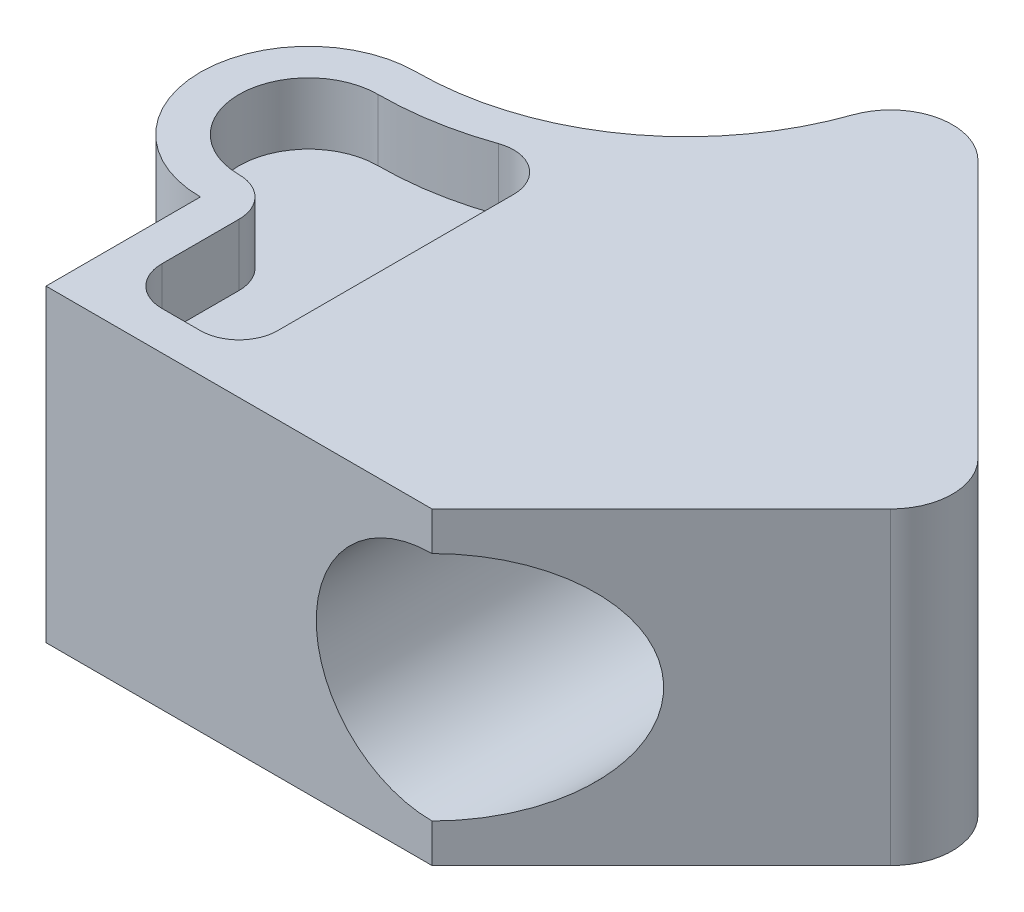
SolidWorks part; units mm, degrees
material "Alliage 1060"
ref_plane "Plan de face" through (0, 0, 0) normal (0, 0, 1) x (1, 0, 0)
ref_plane "Plan de dessus" through (0, 0, 0) normal (0, 1, 0) x (1, 0, 0)
ref_plane "Plan de droite" through (0, 0, 0) normal (1, 0, 0) x (0, 0, -1)
sketch "Esquisse1" plane through (0, 0, 0) normal (0, 1, 0) x (1, 0, 0)
  line L0 (0, 0) -> (50, 0)
  line L1 (50, 0) -> (79.6985, 29.6985)
  line L2 (0, 0) -> (0, 20)
  line L3 (79.6985, 41.0122) -> (46.2469, 74.4637)
  arc A0 (0, 20) -> (0, 48) centre (0, 34) cw
  arc A1 (0, 48) -> (33.0384, 71.4475) centre (0, 83) ccw
  arc A2 (79.6985, 29.6985) -> (79.6985, 41.0122) centre (74.0416, 35.3553) ccw
  arc A3 (46.2469, 74.4637) -> (33.0384, 71.4475) centre (40.5901, 68.8069) ccw
  point P17 (85.3553, 35.3553)
  dimension "D4" = 20
  dimension "D5" = 14
  dimension "D7" = 70
  dimension "D8" = 8
  dimension "D3" = 135
  dimension "D6" = 90
  dimension "D1" = 50
  dimension "D2" = 50
extrude "Boss.-Extru.1" add sketch "Esquisse1" along normal mid plane 40
sketch "Esquisse2" plane through (0, 20, 0) normal (0, 1, 0) x (1, 0, 0)
  line L6 (20, 20) -> (20, 0)
  line L7 (20, 40.5736) -> (20, 10)
  line L8 (5, 26.5167) -> (5, 5)
  line L9 (5, 5) -> (47.9289, 5)
  line L10 (47.9289, 5) -> (76.163, 33.234)
  line L11 (76.163, 37.4767) -> (42.7114, 70.9282)
  line L12 (5, 20) -> (5, 10)
  line L13 (10, 5) -> (15, 5)
  arc A4 (13.3333, 45.2876) -> (20, 40.5736) centre (15, 40.5736) cw
  arc A5 (15, 5) -> (20, 10) centre (15, 10) ccw
  arc A6 (5, 10) -> (10, 5) centre (10, 10) ccw
  arc A7 (5, 20) -> (0, 25) centre (0, 20) ccw
  arc A8 (76.163, 33.234) -> (76.163, 37.4767) centre (74.0416, 35.3553) ccw
  arc A9 (42.7114, 70.9282) -> (37.7582, 69.7971) centre (40.5901, 68.8069) ccw
  arc A10 (0, 43) -> (37.7582, 69.7971) centre (0, 83) ccw
  arc A11 (0, 43) -> (5, 26.5167) centre (0, 34) ccw
  arc A14 (0, 43) -> (13.3333, 45.2876) centre (0, 83) ccw
  arc A15 (0, 43) -> (0, 25) centre (0, 34) ccw
  dimension "D3" = 5
  dimension "D1" = 5
  dimension "D2" = 20
extrude "Enlèv. mat.-Extru.1" cut sketch "Esquisse2" against normal blind 8
sketch "Esquisse3" plane through (0, 0, 0) normal (0, 0, 1) x (1, 0, 0)
  line L0 (-14, 20) -> (-14, -20) construction
  line L1 (50, -20) -> (79.6985, -20) construction
  circle A0 centre (50, 0) radius 15
  circle A1 centre (-14, 0) radius 10
  dimension "D4" = 20
  dimension "D1" = 30
  dimension "D2" = 64
  dimension "D3" = 20
extrude "Enlèv. mat.-Extru.2" cut sketch "Esquisse3" against normal through all
equation "\"A\"= 50"
equation "\"B\"= 10"
equation "\"C\"= \"B\" + 20"
equation "\"D4@Esquisse3\"=\"B\" * 2"
equation "\"D1@Esquisse1\"=\"A\""
equation "\"D1@Esquisse3\"=\"C\""
equation "\"D2@Esquisse1\"=\"A\""
